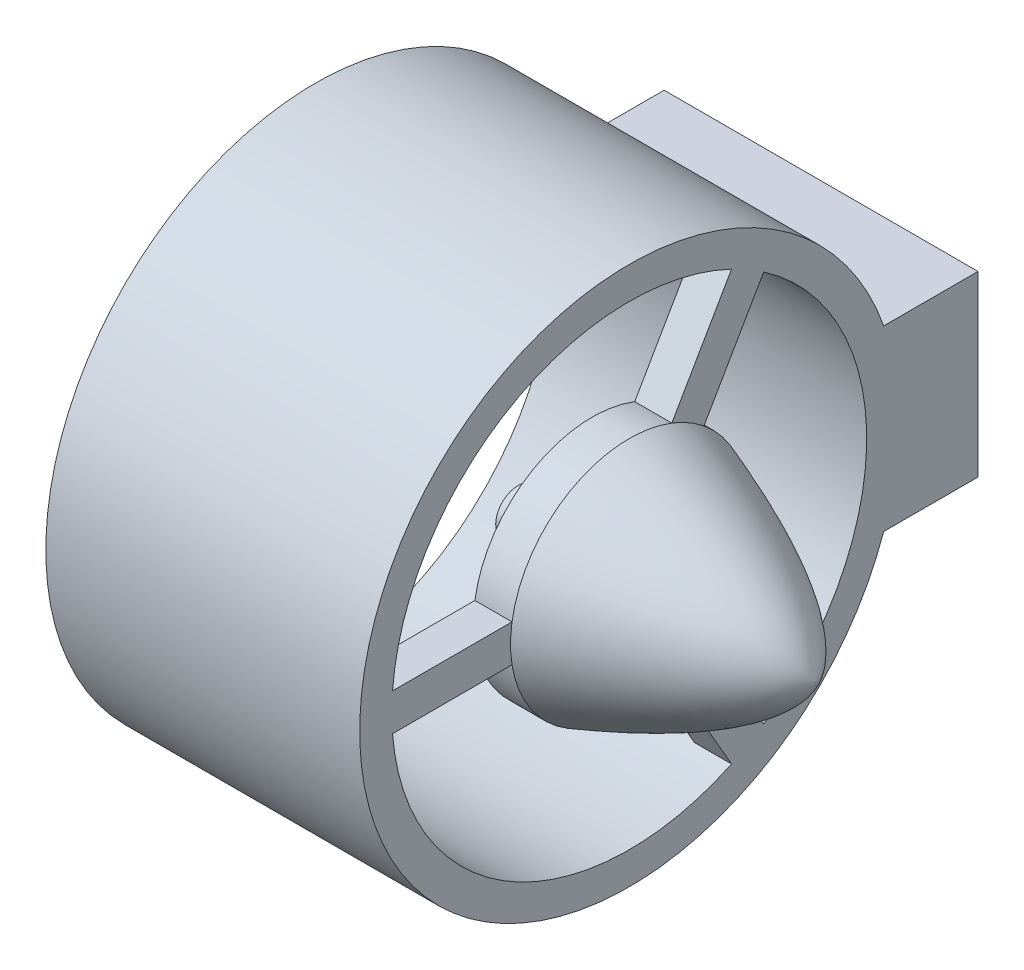
SolidWorks part; units mm, degrees
ref_plane "前视基准面" through (0, 0, 0) normal (0, 0, 1) x (1, 0, 0)
ref_plane "上视基准面" through (0, 0, 0) normal (0, 1, 0) x (1, 0, 0)
ref_plane "右视基准面" through (0, 0, 0) normal (1, 0, 0) x (0, 0, -1)
sketch "草图1" plane through (0, 0, 0) normal (1, 0, 0) x (0, 0, -1)
  line L1 (47, 12) -> (47, -12)
  line L2 (47, 12) -> (34.2909, 12)
  line L3 (47, -12) -> (34.2909, -12)
  line L4 (0, 2.5) -> (-31.9022, 2.5)
  line L6 (0, -2.5) -> (-31.9022, -2.5)
  line L7 (2.1651, -1.25) -> (18.1162, 26.3781)
  line L8 (-2.1651, 1.25) -> (13.786, 28.8781)
  line L11 (2.1651, 1.25) -> (18.1162, -26.3781)
  line L12 (-2.1651, -1.25) -> (13.786, -28.8781)
  circle A0 centre (0, 0) radius 32
  arc A1 (34.2909, 12) -> (34.2909, -12) centre (0, 0) ccw
  circle A2 centre (0, 0) radius 2.5
  circle A3 centre (0, 0) radius 16
sketch "草图2" plane through (0, 0, 0) normal (0, 1, 0) x (1, 0, 0)
  line L0 (0, 0) -> (15, 0)
sketch "草图3" plane through (0, 0, 0) normal (0, 0, 1) x (1, 0, 0)
  line L0 (0, 0) -> (0, -16)
  line L1 (25, 0) -> (0, 0)
  spline S0 degree 2 poles (0, -16) (22.5, -8) (25, 0) knots 0 0 0 1 1 1 construction
  spline S1 degree 2 poles (0, -16) (22.5, -8) (25, 0) knots 0 0 0 1 1 1
revolve "旋转1" add sketch "草图3" angle 360 about L1
extrude "凸台-拉伸1" add sketch "草图1" against normal blind 5 separate body contours L2 A1 L3 L1 A0 | A3 L4 A0 L6 | A3 L7 A0 L8 | A3 L12 A0 L11
sketch "草图5" plane through (0, 0, 0) normal (-1, 0, 0) x (0, 0, 1)
  circle A0 centre (0, 0) radius 16
extrude "凸台-拉伸2" add sketch "草图5" along normal blind 5
sketch "草图7" plane through (-5, 0, 0) normal (-1, 0, 0) x (0, 0, 1)
  line L0 (-34.2909, 12) -> (-47, 12)
  line L1 (-47, 12) -> (-47, -12)
  line L2 (-47, -12) -> (-34.2909, -12)
  circle A0 centre (0, 0) radius 32
  arc A1 (-34.2909, -12) -> (-34.2909, 12) centre (0, 0) ccw
extrude "凸台-拉伸4" add sketch "草图7" along normal blind 37.3
sketch "草图9" plane through (0, 0, -47) normal (0, 0, -1) x (-1, 0, 0)
  line L0 (38.65, -12) -> (38.65, 12)
  line L1 (42.3, -12) -> (0, -12) construction
  line L2 (42.3, 12) -> (0, 12) construction
  line L3 (42.3, 12) -> (42.3, -12) construction
  line L4 (42.3, 4) -> (42.3, -4)
  arc A0 (42.3, -4) -> (42.3, 4) centre (42.6668, 0) cw
  line M4 (42.3, -12) -> (42.3, 12)
extrude "切除-拉伸1" cut sketch "草图9" against normal blind 5 contours A0 M4
sketch "草图10" plane through (0, 0, -47) normal (0, 0, -1) x (-1, 0, 0)
  line L0 (38.65, -12) -> (38.65, 12)
  line L1 (42.3, -12) -> (0, -12) construction
  line L2 (42.3, 12) -> (0, 12) construction
  line L3 (3.65, 12) -> (3.65, -12)
  circle A0 centre (38.65, 8) radius 2
  circle A1 centre (38.65, -8) radius 2
  circle A2 centre (3.65, 8) radius 2
  circle A3 centre (3.65, -8) radius 2
sketch "草图11" plane through (-5, 0, 0) normal (-1, 0, 0) x (0, 0, 1)
  circle A0 centre (0, 0) radius 3
extrude "凸台-拉伸5" add sketch "草图11" along normal blind 10
sketch "草图12" plane through (-42.3, 0, 0) normal (-1, 0, 0) x (0, 0, 1)
  circle A0 centre (34, 0) radius 1
  circle A1 centre (-17, 29.4449) radius 1
  circle A2 centre (-17, -29.4449) radius 1
extrude "切除-拉伸3" cut sketch "草图12" against normal blind 10
hole_wizard "M3 螺纹孔1" positions "草图13" profile "草图14" tap size "M3" standard "GB"
sketch "草图13" plane through (0, 0, -47) normal (0, 0, -1) x (-1, 0, 0)
  point P0 (3.65, -8)
  point P3 (3.65, 8)
  point P6 (38.65, 8)
  point P9 (38.65, -8)
sketch "草图14" plane through (-3.65, -8, -47) normal (1, 0, 0) x (0, 1, 0)
  line L0 (0, 0) -> (0, 15.6511)
  line L1 (0, 15.6511) -> (1.25, 14.9)
  line L2 (1.25, 14.9) -> (1.25, 0)
  line L5 (1.25, 0) -> (0, 0)
  line L10 (0, 15.6511) -> (-1.25, 14.9) construction
  line L11 (0, -6.35) -> (0, 107.95) construction
  dimension "螺纹孔钻头直径" = 2.5
  dimension "螺纹孔钻头深度" = 14.9
  dimension "导头角度" = 118
cosmetic thread "孔螺蚊线1" parameters "D1"=13.4, "D2"=3
cosmetic thread "孔螺蚊线2" parameters "D1"=13.4, "D2"=3
cosmetic thread "孔螺蚊线3" parameters "D1"=13.4, "D2"=3
cosmetic thread "孔螺蚊线4" parameters "D1"=13.4, "D2"=3
